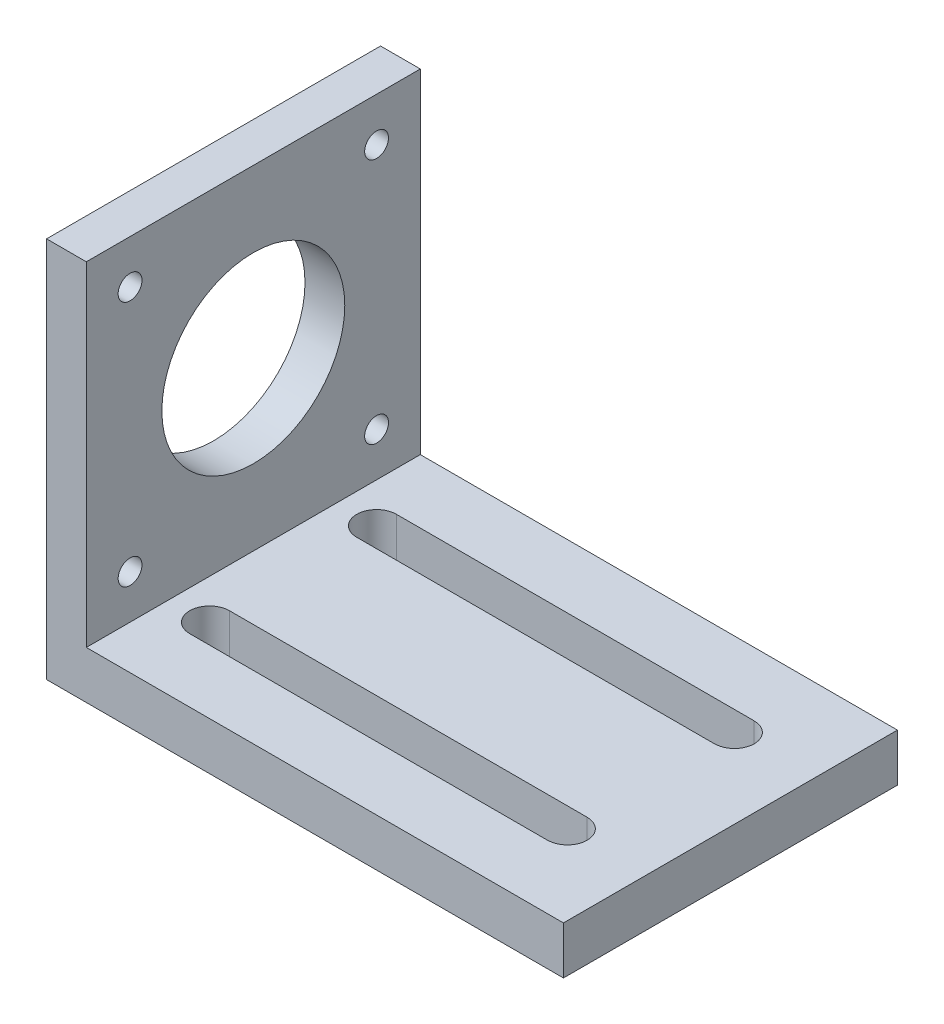
SolidWorks part; units mm, degrees
ref_plane "前视基准面" through (0, 0, 0) normal (0, 0, 1) x (1, 0, 0)
ref_plane "上视基准面" through (0, 0, 0) normal (0, 1, 0) x (1, 0, 0)
ref_plane "右视基准面" through (0, 0, 0) normal (1, 0, 0) x (0, 0, -1)
sketch "草图1" plane through (0, 0, 0) normal (1, 0, 0) x (0, 0, -1)
  line L1 (-48.7093, 21) -> (-6.7093, 21)
  line L2 (-48.7093, 21) -> (-48.7093, -21)
  line L3 (-48.7093, -21) -> (-6.7093, -21)
  line L4 (-6.7093, 21) -> (-6.7093, -21)
  line L5 (-48.7093, 21) -> (-6.7093, -21) construction
  line L6 (-48.7093, -21) -> (-6.7093, 21) construction
  line L11 (-43.2093, 15.5) -> (-12.2093, -15.5) construction
  line L12 (-43.2093, -15.5) -> (-12.2093, 15.5) construction
  circle A0 centre (-12.2093, 15.5) radius 1.5
  circle A1 centre (-43.2093, 15.5) radius 1.5
  circle A2 centre (-12.2093, -15.5) radius 1.5
  circle A3 centre (-43.2093, -15.5) radius 1.5
  point P0 (-27.7093, 0)
  point P5 (-27.7093, 0)
  dimension "D1" = 42
  dimension "D2" = 42
  dimension "D3" = 31
extrude "凸台-拉伸1" add sketch "草图1" along normal blind 5
sketch "草图2" plane through (0, 0, 0) normal (-1, 0, 0) x (0, 0, 1)
  line L1 (6.7093, -21) -> (48.7093, -21)
  line L2 (6.7093, -21) -> (6.7093, -27)
  line L3 (6.7093, -27) -> (48.7093, -27)
  line L4 (48.7093, -21) -> (48.7093, -27)
  dimension "D1" = 42
  dimension "D2" = 6
extrude "凸台-拉伸2" add sketch "草图2" against normal blind 65
sketch "草图3" plane through (0, -27, 0) normal (0, -1, 0) x (-1, 0, 0)
  line L0 (-65, -27.7093) -> (0, -27.7093) construction
  line L1 (-65, -6.7093) -> (-65, -48.7093) construction
  line L2 (0, -6.7093) -> (0, -48.7093) construction
  line L3 (-65, -27.7093) -> (-65, -6.7093) construction
  line L4 (-65, -27.7093) -> (-65, -48.7093) construction
  line L5 (-65, -38.2093) -> (0, -38.2093) construction
  line L6 (-65, -17.2093) -> (0, -17.2093) construction
  line L7 (-10, -19.7093) -> (-55, -19.7093)
  line L8 (-10, -40.7093) -> (-55, -40.7093)
  line L9 (-10, -40.7093) -> (-10, -35.7093)
  line L10 (-10, -35.7093) -> (-55, -35.7093)
  line L11 (-55, -40.7093) -> (-55, -35.7093)
  line L12 (-10, -40.7093) -> (-55, -35.7093) construction
  line L13 (-10, -35.7093) -> (-55, -40.7093) construction
  line L14 (-55, -14.7093) -> (-55, -19.7093)
  line L15 (-10, -14.7093) -> (-55, -14.7093)
  line L16 (-10, -14.7093) -> (-10, -19.7093)
  circle A0 centre (-55, -38.2093) radius 2.4871
  circle A1 centre (-10, -38.2093) radius 2.5
  circle A2 centre (-55, -17.2093) radius 2.4871
  circle A3 centre (-10, -17.2093) radius 2.5
  point P14 (-32.5, -38.2093)
  dimension "D1" = 45
  dimension "D2" = 5
extrude "切除-拉伸2" cut sketch "草图3" against normal blind 65 contours L11 A0 | L11 A0 | A1 L10 L11 A0 L8 | L9 A1 | L9 A1 | A3 L16 | A3 L16 | L7 A3 L15 L14 A2 | A2 L14 | A2 L14
sketch "草图4" plane through (5, 0, 0) normal (1, 0, 0) x (0, 0, -1)
  line L0 (-48.7093, -21) -> (-6.7093, 21) construction
  line L1 (-48.7093, -21) -> (-6.7093, -21) construction
  line L2 (-48.7093, 21) -> (-6.7093, -21) construction
  circle A0 centre (-27.7093, 0) radius 11.5
extrude "切除-拉伸3" cut sketch "草图4" against normal blind 10
